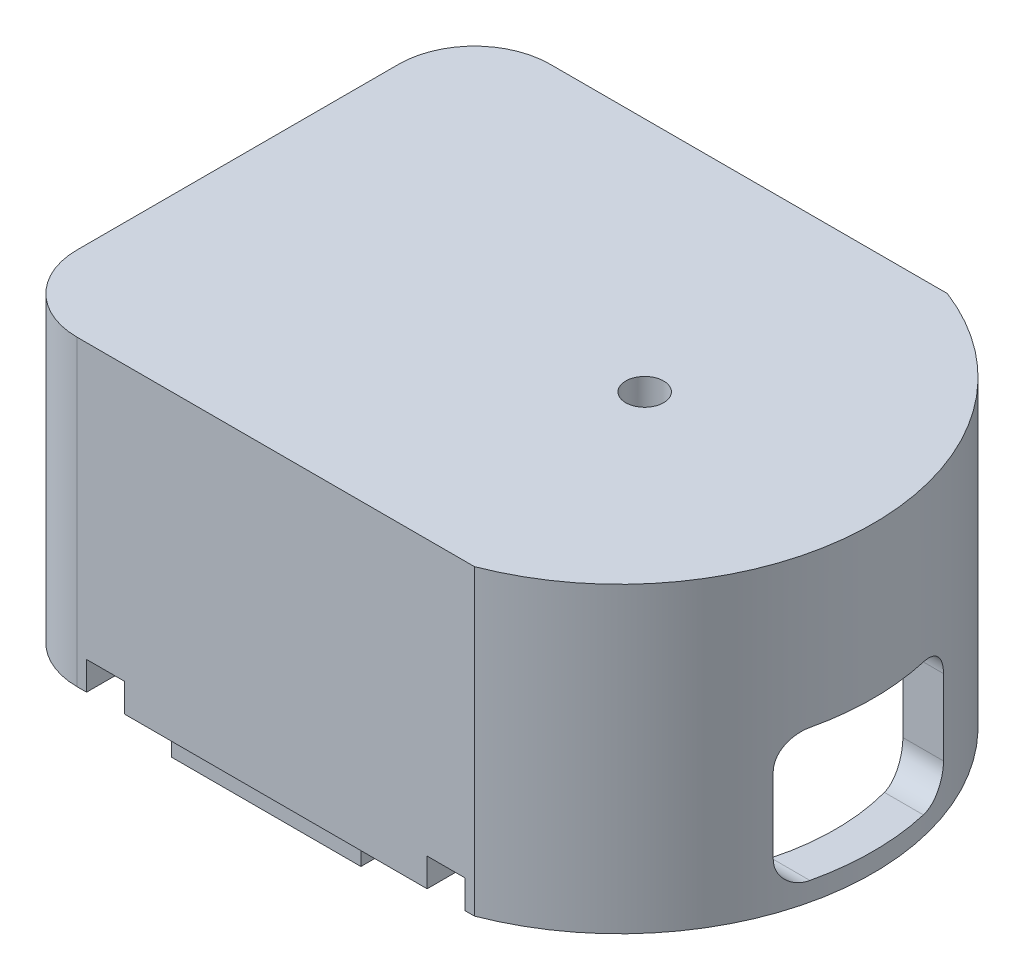
SolidWorks part; units mm, degrees
ref_plane "Ön Düzlem" through (0, 0, 0) normal (0, 0, 1) x (1, 0, 0)
ref_plane "Üst Düzlem" through (0, 0, 0) normal (0, 1, 0) x (1, 0, 0)
ref_plane "Sağ Düzlem" through (0, 0, 0) normal (1, 0, 0) x (0, 0, -1)
sketch "Çizim1" plane through (0, 0, 0) normal (0, 1, 0) x (1, 0, 0)
  line L0 (-127.8643, 125) -> (82.1357, 125)
  line L1 (-167.8643, 85) -> (-167.8643, -85)
  line L2 (-127.8643, -125) -> (82.1357, -125)
  arc A0 (-167.8643, -85) -> (-127.8643, -125) centre (-127.8643, -85) ccw
  arc A1 (-127.8643, 125) -> (-167.8643, 85) centre (-127.8643, 85) ccw
  arc A2 (82.1357, 125) -> (82.1357, -125) centre (33.8694, 0) cw
  point P0 (-86.739, -68.8804)
  dimension "D1" = 40
  dimension "D5" = 133.9949
  dimension "D2" = 250
  dimension "D3" = 250
  dimension "D4" = 250
extrude "Yükseklik-Ekstrüzyon1" add sketch "Çizim1" against normal blind 160
sketch "Çizim2" plane through (0, -160, 0) normal (0, -1, 0) x (1, 0, 0)
  line L9 (-127.8643, -105) -> (78.2523, -105)
  line L10 (-147.8643, 85) -> (-147.8643, -85)
  line L11 (78.2523, 105) -> (-127.8643, 105)
  line L12 (-127.8643, -105) -> (78.2523, -105)
  line L13 (-147.8643, 85) -> (-147.8643, -85)
  line L14 (78.2523, 105) -> (-127.8643, 105)
  arc A9 (78.2523, -105) -> (78.2523, 105) centre (33.8694, 0) ccw
  arc A10 (-147.8643, -85) -> (-127.8643, -105) centre (-127.8643, -85) ccw
  arc A11 (-127.8643, 105) -> (-147.8643, 85) centre (-127.8643, 85) ccw
  arc A12 (78.2523, -105) -> (78.2523, 105) centre (33.8694, 0) ccw
  arc A13 (-147.8643, -85) -> (-127.8643, -105) centre (-127.8643, -85) ccw
  arc A14 (-127.8643, 105) -> (-147.8643, 85) centre (-127.8643, 85) ccw
  dimension "D1" = 20
extrude "Kes-Ekstrüzyon1" cut sketch "Çizim2" against normal blind 140 contours A12 L14 A14 L13 A13 L12
ref_plane "Düzlem1" through (0, -160, 0) normal (0, -1, 0) x (-1, 0, 0)
sketch "Çizim3" plane through (0, -160, 0) normal (0, -1, 0) x (-1, 0, 0)
  line L4 (152.8643, 50) -> (162.8643, 50)
  line L5 (152.8643, 50) -> (152.8643, -50)
  line L6 (152.8643, -50) -> (162.8643, -50)
  line L7 (162.8643, 50) -> (162.8643, -50)
  line L12 (0, -201.4349) -> (0, 240.9769) construction
  line L13 (82.8643, 110) -> (-17.1357, 110)
  line L14 (82.8643, 120) -> (82.8643, 110)
  line L15 (-17.1357, 120) -> (-17.1357, 110)
  line L16 (82.8643, 120) -> (-17.1357, 120)
  line L17 (82.8643, -120) -> (82.8643, -110)
  line L18 (82.8643, -120) -> (-17.1357, -120)
  line L19 (-17.1357, -120) -> (-17.1357, -110)
  line L20 (82.8643, -110) -> (-17.1357, -110)
  line L21 (167.8643, 85) -> (167.8643, -85) construction
  line L22 (127.8643, -125) -> (-82.1357, -125) construction
  line L23 (-82.1357, 125) -> (127.8643, 125) construction
  dimension "D1" = 5
  dimension "D2" = 100
  dimension "D3" = 10
  dimension "D4" = 85
  dimension "D5" = 85
  dimension "D6" = 5
  dimension "D7" = 5
  dimension "D8" = 10
  dimension "D9" = 100
  dimension "D10" = 10
  dimension "D11" = 10
  dimension "D12" = 100
  dimension "D13" = 75
extrude "Yükseklik-Ekstrüzyon2" add sketch "Çizim3" along normal blind 12.3
sketch "Çizim4" plane through (0, 0, 0) normal (0, 1, 0) x (1, 0, 0)
  line L0 (82.1357, 125) -> (-127.8643, 125) construction
  line L2 (-167.8643, 85) -> (-167.8643, -85) construction
  circle A0 centre (47.1357, 0) radius 10
  dimension "D1" = 20
  dimension "D2" = 125
  dimension "D3" = 215
extrude "Kes-Ekstrüzyon2" cut sketch "Çizim4" against normal blind 641.3
ref_plane "Düzlem2" through (62.1357, 0, 0) normal (-1, 0, 0) x (0, 0, 1)
sketch "Çizim6" plane through (62.1357, 0, 0) normal (-1, 0, 0) x (0, 0, 1)
  line L0 (-85, 0) -> (85, 0) construction
  line L1 (-30, -80) -> (30, -80)
  line L2 (-45, -95) -> (-45, -135)
  line L3 (-30, -150) -> (30, -150)
  line L4 (45, -95) -> (45, -135)
  line L5 (125, -160) -> (125, 0) construction
  arc A0 (30, -80) -> (45, -95) centre (30, -95) cw
  arc A1 (30, -150) -> (45, -135) centre (30, -135) ccw
  arc A2 (-45, -135) -> (-30, -150) centre (-30, -135) ccw
  arc A3 (-30, -80) -> (-45, -95) centre (-30, -95) ccw
  dimension "D1" = 15
  dimension "D2" = 90
  dimension "D3" = 70
  dimension "D4" = 80
  dimension "D5" = 80
extrude "Kes-Ekstrüzyon3" cut sketch "Çizim6" against normal blind 641.3
sketch "Çizim7" plane through (0, 0, 125) normal (0, 0, 1) x (1, 0, 0)
  line L0 (-127.8643, -160) -> (82.1357, -160) construction
  line L1 (-122.8643, -145) -> (-102.8643, -145)
  line L2 (-122.8643, -145) -> (-122.8643, -160)
  line L3 (-122.8643, -160) -> (-102.8643, -160)
  line L4 (-102.8643, -145) -> (-102.8643, -160)
  line L5 (-127.8643, -160) -> (-127.8643, 0) construction
  line L6 (57.1357, -145) -> (77.1357, -145)
  line L7 (57.1357, -145) -> (57.1357, -160)
  line L8 (57.1357, -160) -> (77.1357, -160)
  line L9 (77.1357, -145) -> (77.1357, -160)
  line L10 (82.1357, -160) -> (82.1357, 0) construction
  dimension "D1" = 20
  dimension "D2" = 15
  dimension "D3" = 5
  dimension "D4" = 5
  dimension "D5" = 20
  dimension "D6" = 15
extrude "Kes-Ekstrüzyon4" cut sketch "Çizim7" against normal blind 641.3
